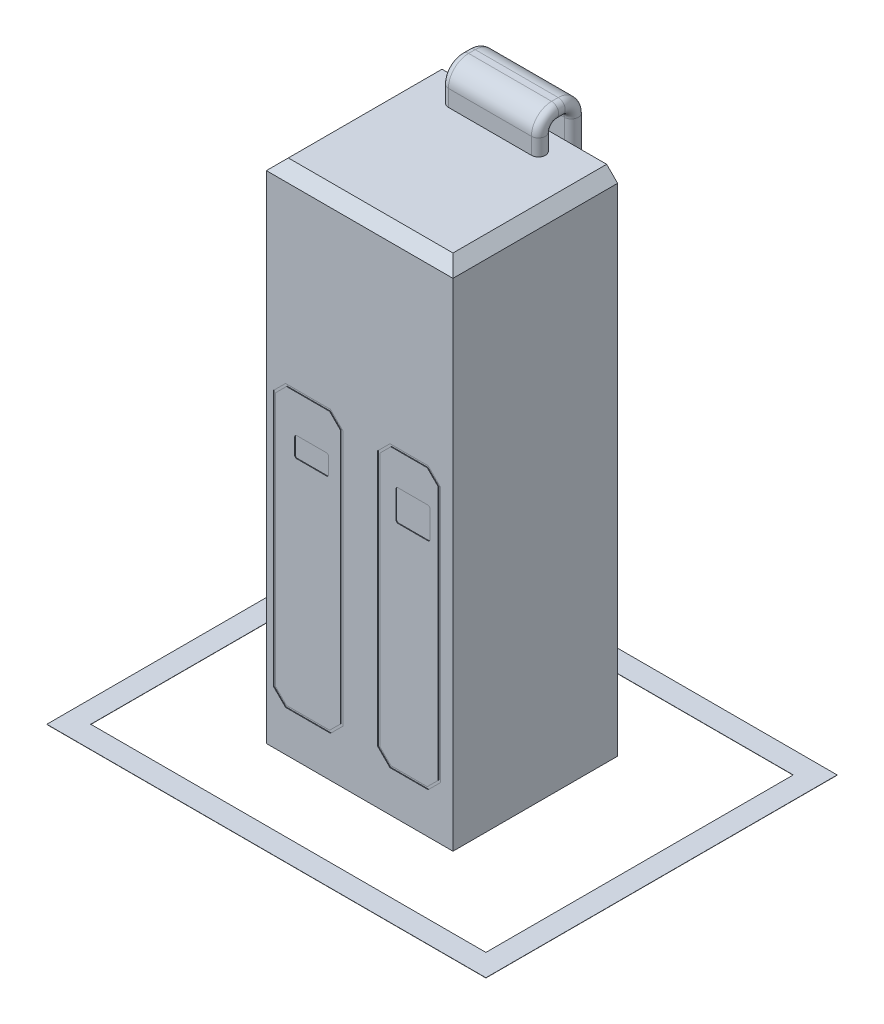
SolidWorks part; units mm, degrees
ref_plane "Alzado" through (0, 0, 0) normal (0, 0, 1) x (1, 0, 0)
ref_plane "Planta" through (0, 0, 0) normal (0, 1, 0) x (1, 0, 0)
ref_plane "Vista lateral" through (0, 0, 0) normal (1, 0, 0) x (0, 0, -1)
sketch "Croquis1" plane through (0, 0, 0) normal (0, 1, 0) x (1, 0, 0)
  line L1 (-425, 375) -> (425, 375)
  line L2 (-425, 375) -> (-425, -375)
  line L3 (-425, -375) -> (425, -375)
  line L4 (425, 375) -> (425, -375)
  line L5 (-425, 375) -> (425, -375) construction
  line L6 (-425, -375) -> (425, 375) construction
  point P0 (0, 0)
  dimension "D1" = 750
  dimension "D2" = 850
extrude "Saliente-Extruir1" add sketch "Croquis1" along normal blind 2310
sketch "Croquis2" plane through (0, 0, 375) normal (0, 0, 1) x (1, 0, 0)
  line L0 (-383.4835, 1404.1171) -> (-333.4835, 1454.1171)
  line L1 (-333.4835, 1454.1171) -> (-136.9229, 1454.1171)
  line L2 (-383.4835, 1404.1171) -> (-383.4835, 246.2913)
  line L3 (-333.4835, 196.2913) -> (-136.9229, 196.2913)
  line L4 (-86.9229, 1404.1171) -> (-86.9229, 246.2913)
  line L5 (-383.4835, 1454.1171) -> (-86.9229, 196.2913) construction
  line L6 (-383.4835, 196.2913) -> (-86.9229, 1454.1171) construction
  line L7 (307.9179, 1454.1171) -> (142.036, 1454.1171)
  line L8 (357.9179, 1404.1171) -> (357.9179, 246.2913)
  line L9 (307.9179, 196.2913) -> (142.036, 196.2913)
  line L10 (92.036, 1404.1171) -> (92.036, 246.2913)
  line L11 (357.9179, 1454.1171) -> (92.036, 196.2913) construction
  line L12 (357.9179, 196.2913) -> (92.036, 1454.1171) construction
  line L13 (-136.9229, 1454.1171) -> (-86.9229, 1404.1171)
  line L14 (-136.9229, 196.2913) -> (-86.9229, 246.2913)
  line L15 (-383.4835, 246.2913) -> (-333.4835, 196.2913)
  line L16 (142.036, 196.2913) -> (92.036, 246.2913)
  line L17 (357.9179, 246.2913) -> (307.9179, 196.2913)
  line L18 (357.9179, 1404.1171) -> (307.9179, 1454.1171)
  line L19 (142.036, 1454.1171) -> (92.036, 1404.1171)
  line L20 (-393.4835, 1408.2592) -> (-393.4835, 242.1492)
  line L21 (-393.4835, 242.1492) -> (-337.6256, 186.2913)
  line L22 (-337.6256, 186.2913) -> (-132.7808, 186.2913)
  line L23 (-132.7808, 186.2913) -> (-76.9229, 242.1492)
  line L24 (-76.9229, 1408.2592) -> (-76.9229, 242.1492)
  line L25 (-132.7808, 1464.1171) -> (-76.9229, 1408.2592)
  line L26 (-337.6256, 1464.1171) -> (-132.7808, 1464.1171)
  line L27 (-393.4835, 1408.2592) -> (-337.6256, 1464.1171)
  line L28 (82.036, 1408.2592) -> (82.036, 242.1492)
  line L29 (137.8939, 186.2913) -> (82.036, 242.1492)
  line L30 (312.06, 186.2913) -> (137.8939, 186.2913)
  line L31 (367.9179, 242.1492) -> (312.06, 186.2913)
  line L32 (367.9179, 1408.2592) -> (367.9179, 242.1492)
  line L33 (367.9179, 1408.2592) -> (312.06, 1464.1171)
  line L34 (312.06, 1464.1171) -> (137.8939, 1464.1171)
  line L35 (137.8939, 1464.1171) -> (82.036, 1408.2592)
  point P0 (-235.2032, 825.2042)
  point P5 (224.977, 825.2042)
  dimension "D1" = 50
  dimension "D2" = 50
  dimension "D3" = 50
  dimension "D4" = 50
  dimension "D5" = 50
  dimension "D6" = 50
  dimension "D7" = 50
  dimension "D8" = 50
  dimension "D9" = 50
  dimension "D10" = 50
  dimension "D11" = 50
  dimension "D12" = 50
  dimension "D13" = 50
  dimension "D14" = 50
  dimension "D15" = 50
  dimension "D16" = 50
  dimension "D17" = 10
extrude "Cortar-Extruir1" cut sketch "Croquis2" against normal blind 3
sketch "Croquis3" plane through (0, 0, 375) normal (0, 0, 1) x (1, 0, 0)
  line L1 (-286.091, 1283.9189) -> (-151.1044, 1283.9189)
  line L2 (-296.091, 1273.9189) -> (-296.091, 1202.3359)
  line L3 (-286.091, 1192.3359) -> (-151.1044, 1192.3359)
  line L4 (-141.1044, 1273.9189) -> (-141.1044, 1202.3359)
  line L5 (-296.091, 1283.9189) -> (-141.1044, 1192.3359) construction
  line L6 (-296.091, 1192.3359) -> (-141.1044, 1283.9189) construction
  line L7 (175.3464, 1308.5759) -> (310.3331, 1308.5759)
  line L8 (165.3464, 1298.5759) -> (165.3464, 1177.6789)
  line L9 (175.3464, 1167.6789) -> (310.3331, 1167.6789)
  line L10 (320.3331, 1298.5759) -> (320.3331, 1177.6789)
  line L11 (165.3464, 1308.5759) -> (320.3331, 1167.6789) construction
  line L12 (165.3464, 1167.6789) -> (320.3331, 1308.5759) construction
  arc A0 (175.3464, 1308.5759) -> (165.3464, 1298.5759) centre (175.3464, 1298.5759) ccw
  arc A1 (310.3331, 1308.5759) -> (320.3331, 1298.5759) centre (310.3331, 1298.5759) cw
  arc A2 (310.3331, 1167.6789) -> (320.3331, 1177.6789) centre (310.3331, 1177.6789) ccw
  arc A3 (165.3464, 1177.6789) -> (175.3464, 1167.6789) centre (175.3464, 1177.6789) ccw
  arc A4 (-151.1044, 1283.9189) -> (-141.1044, 1273.9189) centre (-151.1044, 1273.9189) cw
  arc A5 (-151.1044, 1192.3359) -> (-141.1044, 1202.3359) centre (-151.1044, 1202.3359) ccw
  arc A6 (-296.091, 1202.3359) -> (-286.091, 1192.3359) centre (-286.091, 1202.3359) ccw
  arc A7 (-286.091, 1283.9189) -> (-296.091, 1273.9189) centre (-286.091, 1273.9189) ccw
  point P0 (-218.5977, 1238.1274)
  point P5 (242.8398, 1238.1274)
  dimension "D1" = 10
extrude "Cortar-Extruir2" cut sketch "Croquis3" against normal blind 3
sketch "Croquis4" plane through (-425, 0, 0) normal (-1, 0, 0) x (0, 0, 1)
  line L0 (0, 1691.8679) -> (0, 898.7038) construction
  line L1 (109.212, 1691.8679) -> (109.212, 898.7038)
  line L2 (-109.212, 1691.8679) -> (-109.212, 898.7038)
  arc A0 (109.212, 1691.8679) -> (-109.212, 1691.8679) centre (0, 1691.8679) ccw
  arc A1 (-109.212, 898.7038) -> (109.212, 898.7038) centre (0, 898.7038) ccw
  point P3 (0, 1295.2859)
extrude "Cortar-Extruir3" cut sketch "Croquis4" against normal blind 3
sketch "Croquis5" plane through (-425, 0, 0) normal (-1, 0, 0) x (0, 0, 1)
  line L0 (201.8687, 1968.2124) -> (211.8687, 2018.2124)
  line L1 (-181.8687, 2171.909) -> (181.8687, 2171.909)
  line L2 (-211.8687, 2121.909) -> (-211.8687, 1998.2124)
  line L3 (-161.8687, 1968.2124) -> (201.8687, 1968.2124)
  line L4 (211.8687, 2121.909) -> (211.8687, 2018.2124)
  line L5 (-211.8687, 2171.909) -> (211.8687, 1968.2124) construction
  line L6 (-211.8687, 1968.2124) -> (211.8687, 2171.909) construction
  line L7 (181.8687, 2171.909) -> (211.8687, 2121.909)
  line L8 (-211.8687, 2121.909) -> (-181.8687, 2171.909)
  line L9 (-211.8687, 1998.2124) -> (-161.8687, 1968.2124)
  point P0 (0, 2070.0607)
  dimension "D1" = 10
  dimension "D2" = 50
  dimension "D3" = 30
  dimension "D4" = 50
  dimension "D5" = 30
  dimension "D6" = 50
  dimension "D7" = 30
  dimension "D8" = 50
extrude "Cortar-Extruir4" cut sketch "Croquis5" against normal blind 3
sketch "Croquis6" plane through (0, 2310, 0) normal (0, 1, 0) x (1, 0, 0)
  line L0 (168.3896, 270.9286) -> (-209.7815, 270.9286) construction
  line L1 (168.3896, 238.944) -> (-209.7815, 238.944)
  line L2 (168.3896, 302.9132) -> (-209.7815, 302.9132)
  arc A0 (168.3896, 238.944) -> (168.3896, 302.9132) centre (168.3896, 270.9286) ccw
  arc A1 (-209.7815, 302.9132) -> (-209.7815, 238.944) centre (-209.7815, 270.9286) ccw
  point P2 (-20.6959, 270.9286)
sketch3d "Croquis3D1"
  line L0 (-20.6959, 2310, -270.9286) -> (-20.6959, 2385.0143, -270.9286)
  line L1 (-20.6959, 2445.0143, -330.9286) -> (-20.6959, 2445.0143, -360.9286)
  line L2 (-20.6959, 2385.0143, -420.9286) -> (-20.6959, 94.914, -420.9286)
  arc A0 (-20.6959, 2445.0143, -360.9286) -> (-20.6959, 2385.0143, -420.9286) centre (-20.6959, 2385.0143, -360.9286) ccw
  arc A1 (-20.6959, 2385.0143, -270.9286) -> (-20.6959, 2445.0143, -330.9286) centre (-20.6959, 2385.0143, -330.9286) ccw
  point P7 (-20.6959, 2445.0143, -420.9286)
  point P8 (-80.6959, 2385.0143, -360.9286)
  point P11 (-20.6959, 2445.0143, -270.9286)
  point P12 (-80.6959, 2385.0143, -330.9286)
  dimension "D2" = 60
  dimension "D1" = 150
sweep "Barrer1" add profiles "Croquis6" path "Croquis3D1"
chamfer "Chaflán1" distance 50 angle 45 3 edges at (425, 2310, 0) (-425, 2310, 0) (0, 2310, 375)
sketch "Croquis7" plane through (0, 0, 0) normal (0, 1, 0) x (1, 0, 0)
  line L0 (-900, 700) -> (-900, -700)
  line L1 (-1000, 800) -> (1000, 800)
  line L2 (-1000, 800) -> (-1000, -800)
  line L3 (-1000, -800) -> (1000, -800)
  line L4 (1000, 800) -> (1000, -800)
  line L5 (-1000, 800) -> (1000, -800) construction
  line L6 (-1000, -800) -> (1000, 800) construction
  line L7 (-900, -700) -> (900, -700)
  line L8 (900, 700) -> (900, -700)
  line L9 (-900, 700) -> (900, 700)
  point P0 (0, 0)
  dimension "D1" = 2000
  dimension "D2" = 1600
  dimension "D3" = 100
extrude "Saliente-Extruir2" add sketch "Croquis7" along normal blind 1 separate body
